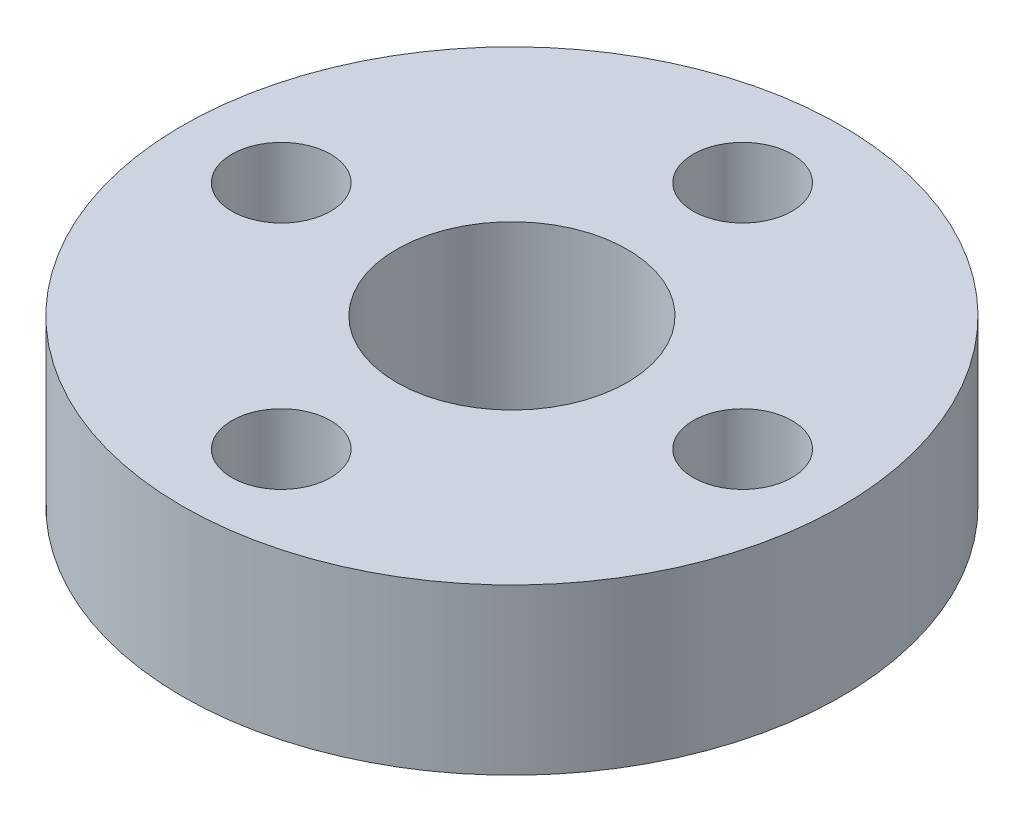
SolidWorks part; units mm, degrees
ref_plane "前视基准面" through (0, 0, 0) normal (0, 0, 1) x (1, 0, 0)
ref_plane "上视基准面" through (0, 0, 0) normal (0, 1, 0) x (1, 0, 0)
ref_plane "右视基准面" through (0, 0, 0) normal (1, 0, 0) x (0, 0, -1)
other "Configuration Table"
sketch "草图1" plane through (0, 0, 0) normal (0, 1, 0) x (1, 0, 0)
  line L0 (0, 0) -> (0, 14.2124) construction
  line L1 (0, 0) -> (17.2087, 0) construction
  circle A0 centre (0, 0) radius 10
  circle A1 centre (0, 7) radius 1.5
  circle A2 centre (7, 0) radius 1.5
  circle A3 centre (0, 0) radius 3.5
  circle A4 centre (0, -7) radius 1.5
  circle A5 centre (-7, 0) radius 1.5
  dimension "D1" = 20
  dimension "D2" = 3
  dimension "D3" = 3
  dimension "D4" = 7
  dimension "D5" = 7
  dimension "D6" = 7
extrude "凸台-拉伸1" add sketch "草图1" along normal blind 5
